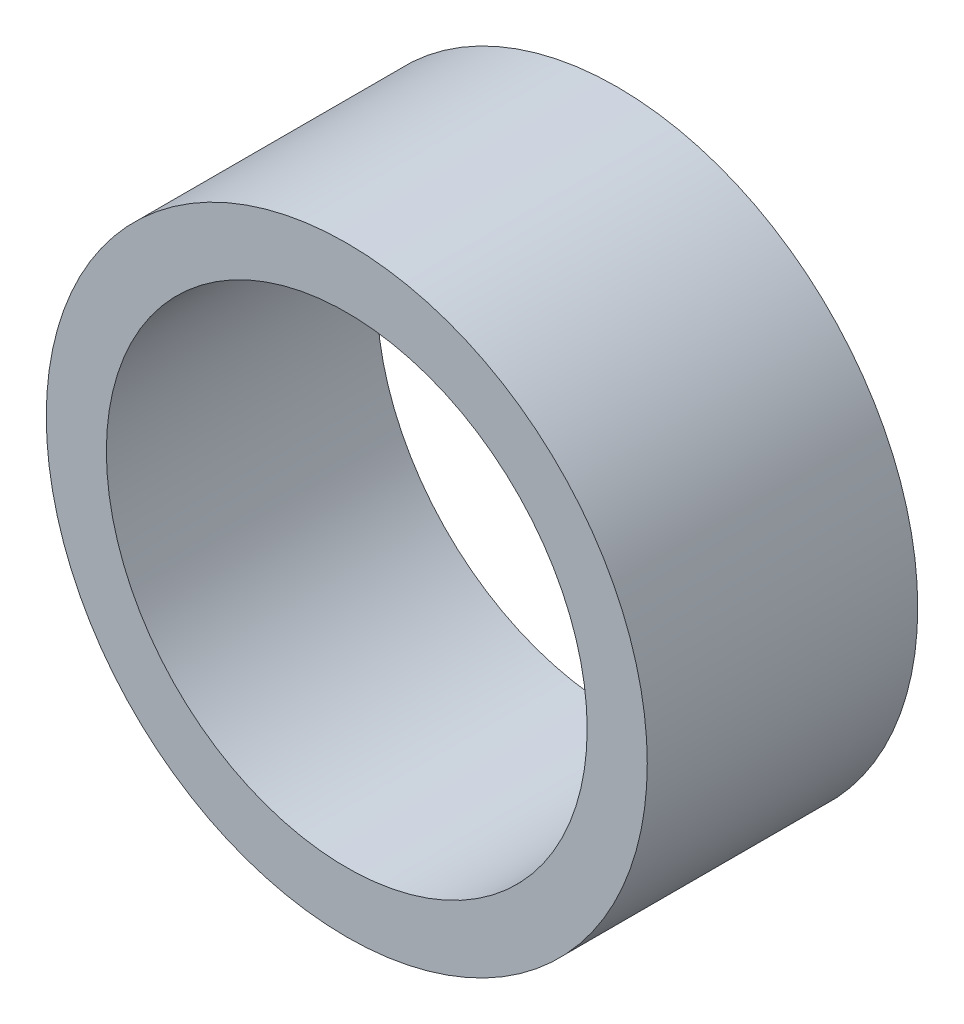
SolidWorks part; units mm, degrees
ref_plane "Front Plane" through (0, 0, 0) normal (0, 0, 1) x (1, 0, 0)
ref_plane "Top Plane" through (0, 0, 0) normal (0, 1, 0) x (1, 0, 0)
ref_plane "Right Plane" through (0, 0, 0) normal (1, 0, 0) x (0, 0, -1)
sketch "Sketch1" plane through (0, 0, 0) normal (0, 0, 1) x (1, 0, 0)
  circle A0 centre (0, 0) radius 12.7
  dimension "D1" = 25.4
extrude "Boss-Extrude1" add sketch "Sketch1" along normal blind 11.43
sketch "Sketch2" plane through (0, 0, 11.43) normal (0, 0, 1) x (1, 0, 0)
  circle A0 centre (0, 0) radius 10.16
  circle A1 centre (0, 0) radius 12.7 construction
  dimension "D1" = 2.54
extrude "Cut-Extrude1" cut sketch "Sketch2" against normal through all
